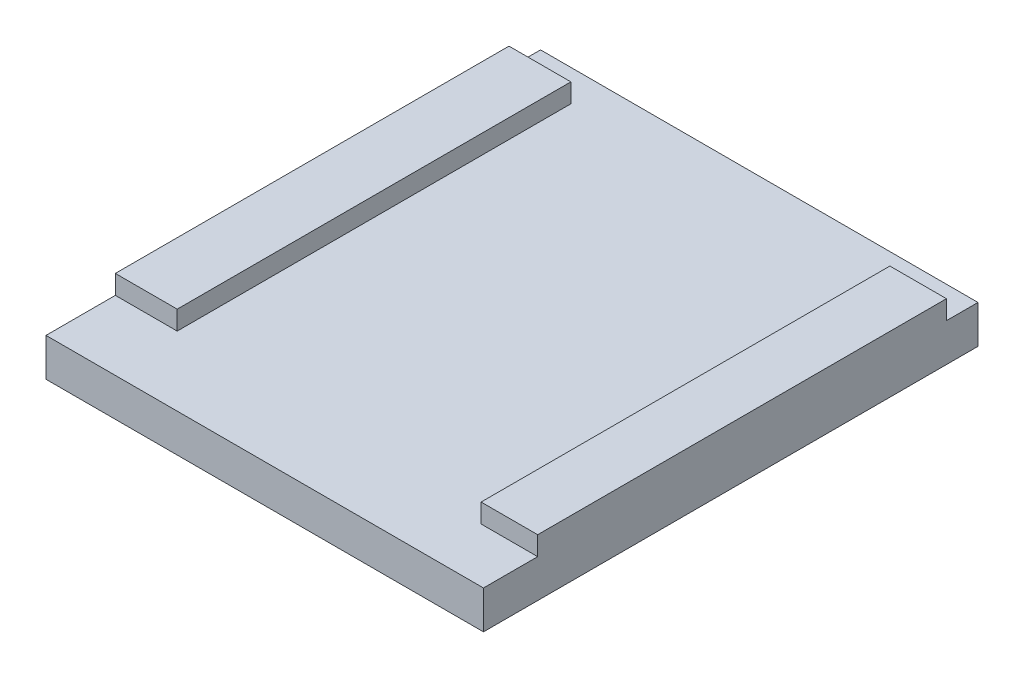
SolidWorks part; units mm, degrees
ref_plane "Front Plane" through (0, 0, 0) normal (0, 0, 1) x (1, 0, 0)
ref_plane "Top Plane" through (0, 0, 0) normal (0, 1, 0) x (1, 0, 0)
ref_plane "Right Plane" through (0, 0, 0) normal (1, 0, 0) x (0, 0, -1)
sketch "Sketch1" plane through (0, 0, 0) normal (0, 1, 0) x (1, 0, 0)
  line L1 (0, 0) -> (23, 0)
  line L2 (0, 0) -> (0, -26)
  line L3 (0, -26) -> (23, -26)
  line L4 (23, 0) -> (23, -26)
  dimension "D1" = 23
  dimension "D2" = 26
extrude "Boss-Extrude1" add sketch "Sketch1" along normal blind 2
sketch "Sketch2" plane through (0, 2, 0) normal (0, 1, 0) x (1, 0, 0)
  line L0 (0, 0) -> (0, -26) construction
  line L1 (0, -1.6588) -> (3.254, -1.6588)
  line L2 (0, -1.6588) -> (0, -22.3556)
  line L3 (0, -22.3556) -> (3.254, -22.3556)
  line L4 (3.254, -1.6588) -> (3.254, -22.3556)
  line L5 (23, -26) -> (23, 0) construction
  line L6 (23, -1.6588) -> (20.0263, -1.6588)
  line L7 (23, -1.6588) -> (23, -23.1498)
  line L8 (23, -23.1498) -> (20.0263, -23.1498)
  line L9 (20.0263, -1.6588) -> (20.0263, -23.1498)
extrude "Boss-Extrude2" add sketch "Sketch2" along normal blind 1
